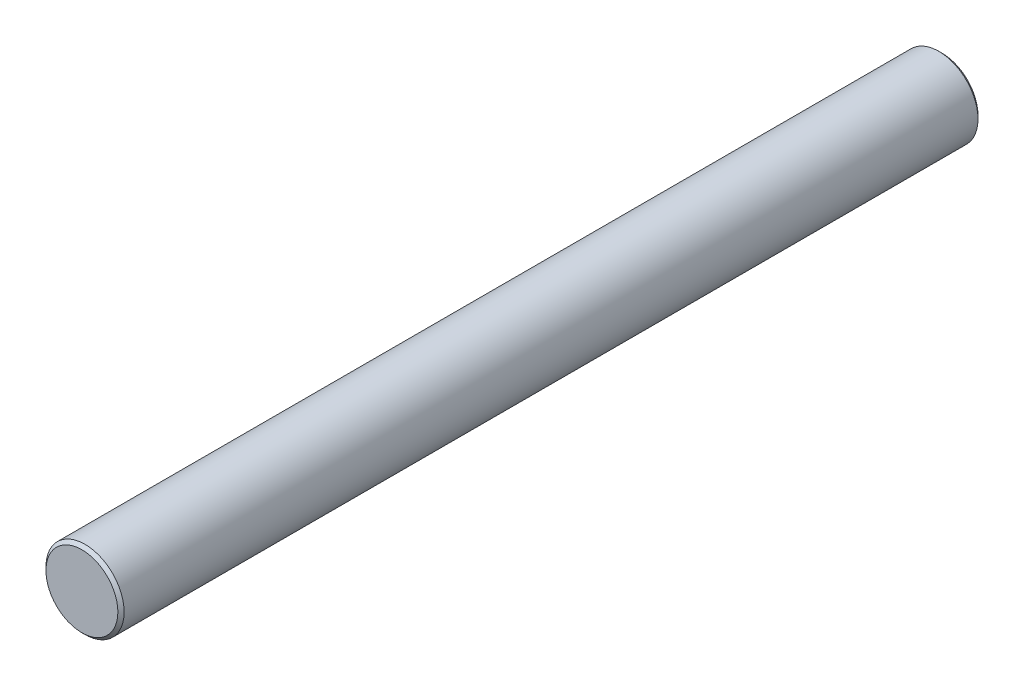
SolidWorks part; units mm, degrees
material "Vero PureWhite"
ref_plane "前视基准面" through (0, 0, 0) normal (0, 0, 1) x (1, 0, 0)
ref_plane "上视基准面" through (0, 0, 0) normal (0, 1, 0) x (1, 0, 0)
ref_plane "右视基准面" through (0, 0, 0) normal (1, 0, 0) x (0, 0, -1)
sketch "草图1" plane through (0, 0, 0) normal (0, 0, 1) x (1, 0, 0)
  circle A0 centre (0, 0) radius 2.5
  dimension "D1" = 5
extrude "凸台-拉伸1" add sketch "草图1" along normal blind 55
chamfer "倒角1" distance 0.2 angle 45 2 edges at (2.5, 0, 0) (2.5, 0, 55)
scale "缩放比例1" scale about origin uniform scaling yes scale factor 0.6
